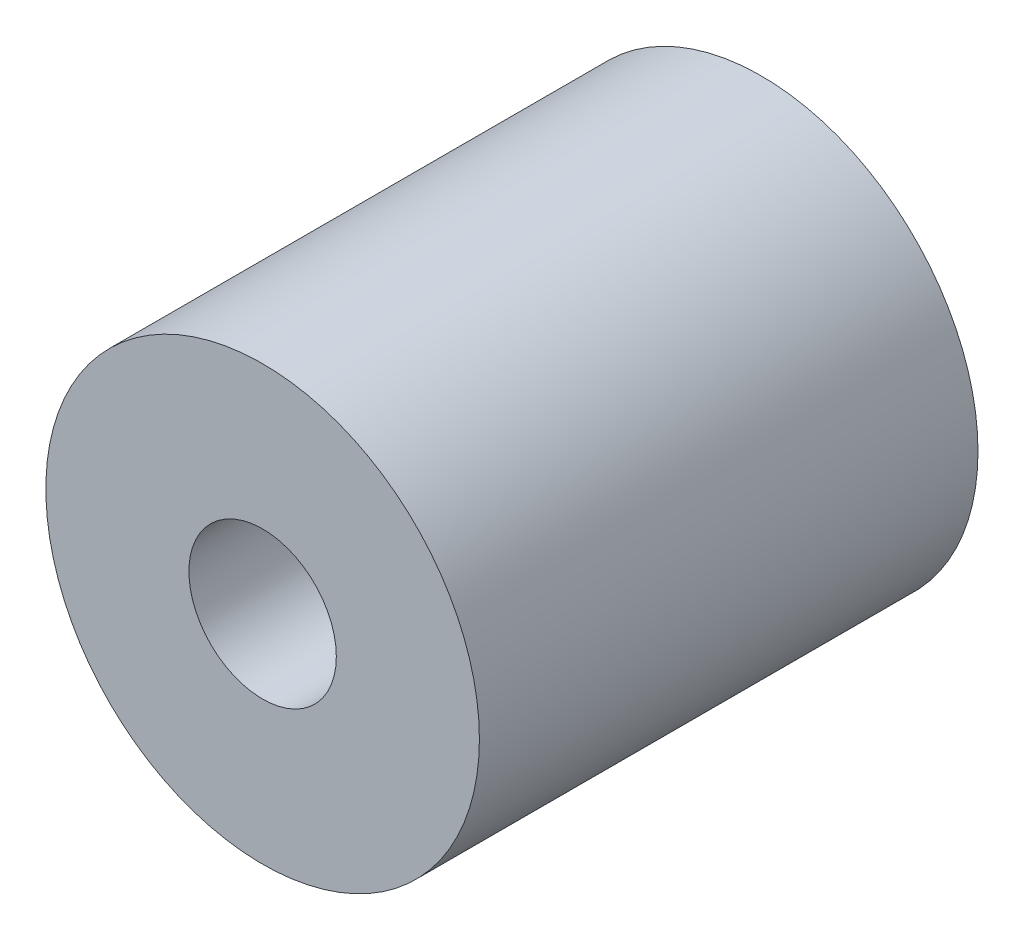
SolidWorks part; units mm, degrees
material "PET"
ref_plane "Front Plane" through (0, 0, 0) normal (0, 0, 1) x (1, 0, 0)
ref_plane "Top Plane" through (0, 0, 0) normal (0, 1, 0) x (1, 0, 0)
ref_plane "Right Plane" through (0, 0, 0) normal (1, 0, 0) x (0, 0, -1)
sketch "Sketch1" plane through (0, 0, 0) normal (0, 0, 1) x (1, 0, 0)
  circle A0 centre (0, 0) radius 5
  circle A1 centre (0, 0) radius 1.7
  dimension "D1" = 3.4
  dimension "D2" = 10
extrude "Boss-Extrude1" add sketch "Sketch1" along normal blind 11.5
